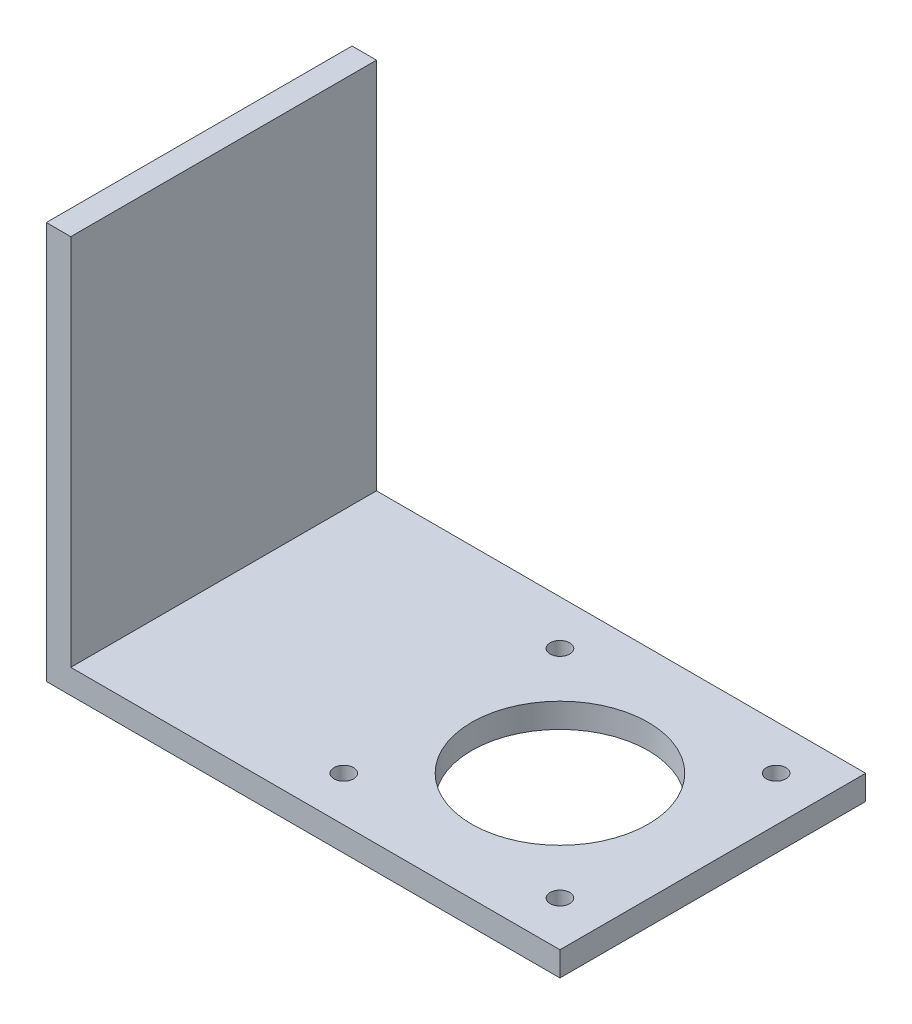
SolidWorks part; units mm, degrees
ref_plane "前视基准面" through (0, 0, 0) normal (0, 0, 1) x (1, 0, 0)
ref_plane "上视基准面" through (0, 0, 0) normal (0, 1, 0) x (1, 0, 0)
ref_plane "右视基准面" through (0, 0, 0) normal (1, 0, 0) x (0, 0, -1)
sketch "草图1" plane through (0, 0, 0) normal (0, 1, 0) x (1, 0, 0)
  line L1 (-25, 25) -> (25, 25)
  line L2 (-25, 25) -> (-25, -25)
  line L3 (-25, -25) -> (25, -25)
  line L4 (25, 25) -> (25, -25)
  line L5 (-25, 25) -> (25, -25) construction
  line L6 (-25, -25) -> (25, 25) construction
  circle A4 centre (0, 0) radius 14.4369
  circle A5 centre (-17.6777, -17.6777) radius 1.6
  circle A6 centre (17.6777, -17.6777) radius 1.6
  circle A7 centre (17.6777, 17.6777) radius 1.6
  circle A8 centre (-17.6777, 17.6777) radius 1.6
  point P0 (0, 0)
  point P5 (-17.6777, -17.6777)
  point P9 (17.6777, -17.6777)
  point P16 (17.6777, 17.6777)
  point P17 (-17.6777, 17.6777)
  dimension "D1" = 50
  dimension "D2" = 50
  dimension "D3" = 25
  dimension "D4" = 25
  dimension "D5" = 25
  dimension "D6" = 25
extrude "凸台-拉伸1" add sketch "草图1" along normal blind 4
sketch "草图2" plane through (0, 0, 0) normal (0, 1, 0) x (1, 0, 0)
  line L0 (-25, 25) -> (-56, 25)
  line L1 (-25, -25) -> (-56, -25)
  line L2 (-56, -25) -> (-56, 25)
  line L3 (-25, 25) -> (-25, -25)
extrude "凸台-拉伸2" add sketch "草图2" along normal blind 4
ref_plane "基准面4" through (-55, 0, 0) normal (-1, 0, 0) x (0, 0, 1)
sketch "草图3" plane through (-55, 0, 0) normal (-1, 0, 0) x (0, 0, 1)
  line L0 (-25, 0) -> (-25, 65)
  line L1 (25, 0) -> (25, 65)
  line L3 (-25, 0) -> (25, 0)
  line L4 (-25, 65) -> (25, 65)
extrude "凸台-拉伸3" add sketch "草图3" along normal blind 4
